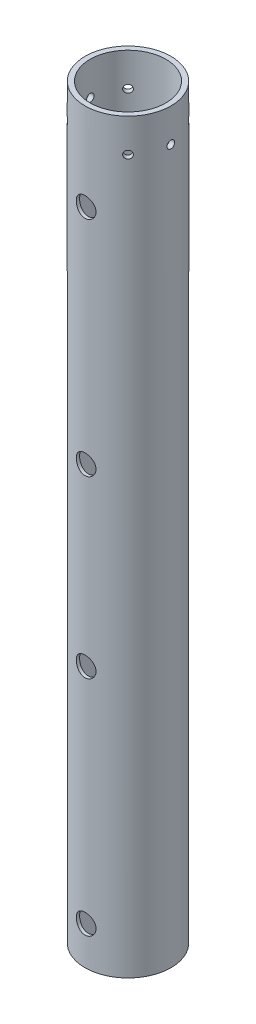
SolidWorks part; units mm, degrees
ref_plane "前视基准面" through (0, 0, 0) normal (0, 0, 1) x (1, 0, 0)
ref_plane "上视基准面" through (0, 0, 0) normal (0, 1, 0) x (1, 0, 0)
ref_plane "右视基准面" through (0, 0, 0) normal (1, 0, 0) x (0, 0, -1)
sketch "草图1" plane through (0, 0, 0) normal (0, 1, 0) x (1, 0, 0)
  circle A0 centre (0, 0) radius 125
  circle A1 centre (0, 0) radius 135
  dimension "D1" = 270
  dimension "D2" = 250
extrude "凸台-拉伸1" add sketch "草图1" along normal blind 2335
sketch "草图2" plane through (0, 0, 0) normal (0, 0, 1) x (1, 0, 0)
  line L0 (0, -1000) -> (0, 49000) construction
  line L1 (0, 0) -> (135, 0)
  line L2 (135, 0) -> (135, -10)
  line L3 (0, 0) -> (0, -30)
  line L4 (135, 0) -> (135, 2335) construction
  arc A0 (135, -10) -> (0, -30) centre (0, 435.625) cw
  dimension "D1" = 30
  dimension "D2" = 10
revolve "旋转1" add sketch "草图2" angle 360 about L0
sketch "草图3" plane through (0, 0, 0) normal (0, 1, 0) x (1, 0, 0)
  line L0 (-1000, 0) -> (49000, 0) construction
  line L1 (0, -1000) -> (0, 49000) construction
  line L2 (-124.9, 5) -> (-50, 5)
  line L3 (-50, 5) -> (-50, 114.5644)
  line L5 (-40, 118.4272) -> (-40, 5)
  line L6 (-40, 5) -> (40, 5)
  line L7 (40, 5) -> (40, 118.4272)
  line L9 (50, 114.5644) -> (50, 5)
  line L10 (50, 5) -> (124.9, 5)
  line L12 (124.9, -5) -> (50, -5)
  line L13 (50, -5) -> (50, -114.5644)
  line L15 (40, -118.4272) -> (40, -5)
  line L16 (40, -5) -> (-40, -5)
  line L17 (-40, -5) -> (-40, -118.4272)
  line L19 (-50, -114.5644) -> (-50, -5)
  line L20 (-50, -5) -> (-124.9, -5)
  circle A0 centre (0, 0) radius 125 construction
  circle A1 centre (0, 0) radius 125 construction
  arc A2 (-124.9, 5) -> (-124.9, -5) centre (0, 0) ccw
  arc A3 (-50, -114.5644) -> (-40, -118.4272) centre (0, 0) ccw
  arc A4 (40, -118.4272) -> (50, -114.5644) centre (0, 0) ccw
  arc A5 (124.9, 5) -> (124.9, -5) centre (0, 0) cw
  arc A6 (40, 118.4272) -> (50, 114.5644) centre (0, 0) cw
  arc A7 (-50, 114.5644) -> (-40, 118.4272) centre (0, 0) cw
  dimension "D1" = 10
  dimension "D2" = 80
  dimension "D3" = 10
extrude "凸台-拉伸4" add sketch "草图3" along normal blind 250
ref_plane "基准面1" through (0, 0, 500) normal (0, 0, 1) x (1, 0, 0)
sketch "草图4" plane through (0, 0, 500) normal (0, 0, 1) x (1, 0, 0)
  line L0 (0, 1124) -> (0, 51124) construction
  line L1 (125, 2335) -> (-125, 2335) construction
  circle A0 centre (0, 2060) radius 31
  circle A1 centre (0, 1360) radius 31
  circle A2 centre (0, 110) radius 31
  circle A3 centre (0, 810) radius 31
  point P5 (0, 2335)
  dimension "D1" = 62
  dimension "D2" = 275
  dimension "D3" = 700
  dimension "D4" = 700
  dimension "D5" = 550
extrude "切除-拉伸1" cut sketch "草图4" against normal through all
sketch "草图5" plane through (0, 2335, 0) normal (0, 1, 0) x (1, 0, 0)
  circle A0 centre (0, 0) radius 119
  circle A1 centre (0, 0) radius 125
  arc A2 (-40, -118.4272) -> (40, -118.4272) centre (0, 0) ccw construction
  arc A3 (-124.9, -5) -> (-50, -114.5644) centre (0, 0) ccw construction
  dimension "D1" = 238
extrude "凸台-拉伸5" add sketch "草图5" against normal blind 210
ref_plane "基准面7" through (-250, 0, 250) normal (0.7071, 0, -0.7071) x (-0.7071, 0, -0.7071)
ref_plane "基准面8" through (250, 0, 250) normal (0.7071, 0, 0.7071) x (0.7071, 0, -0.7071)
ref_plane "基准面10" through (500, 0, 0) normal (1, 0, 0) x (0, 0, -1)
sketch "草图7" plane through (-250, 0, 250) normal (0.7071, 0, -0.7071) x (-0.7071, 0, -0.7071)
  line L0 (0, -1000) -> (0, 49000) construction
  line L1 (119, 2335) -> (-119, 2335) construction
  circle A0 centre (0, 2230) radius 12
  dimension "D1" = 24
  dimension "D2" = 105
extrude "切除-拉伸3" cut sketch "草图7" along normal through all
sketch "草图8" plane through (250, 0, 250) normal (0.7071, 0, 0.7071) x (0.7071, 0, -0.7071)
  line L0 (0, -1000) -> (0, 49000) construction
  line L1 (119, 2335) -> (-119, 2335) construction
  circle A0 centre (0, 2230) radius 12
  dimension "D2" = 24
  dimension "D1" = 105
extrude "切除-拉伸4" cut sketch "草图8" against normal through all
sketch "草图9" plane through (500, 0, 0) normal (1, 0, 0) x (0, 0, -1)
  line L0 (0, -1010) -> (0, 48990) construction
  line L1 (-135, -10) -> (135, -10) construction
  line L2 (135, 2335) -> (-135, 2335) construction
  circle A0 centre (0, 2230) radius 12
  point P5 (0, -10)
  dimension "D2" = 24
  dimension "D1" = 105
extrude "切除-拉伸5" cut sketch "草图9" against normal through all
